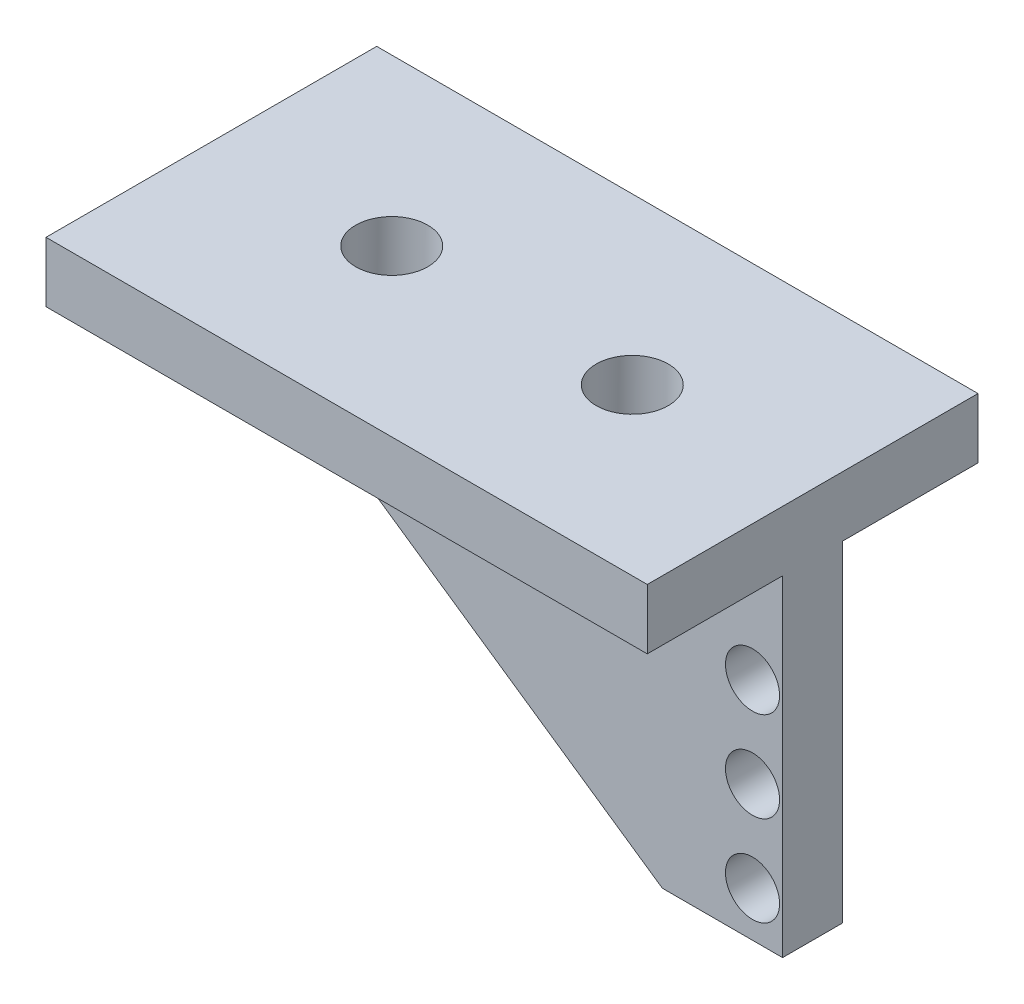
SolidWorks part; units mm, degrees
ref_plane "Front Plane" through (0, 0, 0) normal (0, 0, 1) x (1, 0, 0)
ref_plane "Top Plane" through (0, 0, 0) normal (0, 1, 0) x (1, 0, 0)
ref_plane "Right Plane" through (0, 0, 0) normal (1, 0, 0) x (0, 0, -1)
sketch "Sketch1" plane through (0, 0, 0) normal (0, 1, 0) x (1, 0, 0)
  line L0 (-20, 5.5) -> (0, 5.5)
  line L1 (0, 5.5) -> (0, -5.5)
  line L2 (0, -5.5) -> (-20, -5.5)
  line L3 (-20, -5.5) -> (-20, 5.5)
extrude "Boss-Extrude1" add sketch "Sketch1" against normal blind 2
ref_plane "Plane1" through (0, 0, -1) normal (0, 0, 1) x (1, 0, 0)
sketch "Sketch2" plane through (0, 0, -1) normal (0, 0, 1) x (1, 0, 0)
  line L0 (0, 0) -> (0, -13)
  line L1 (0, -13) -> (-4, -13)
  line L2 (-4, -13) -> (-20, -2)
  line L3 (-20, -2) -> (-20, 0)
  line L4 (-20, 0) -> (0, 0)
extrude "Boss-Extrude2" add sketch "Sketch2" along normal blind 2
ref_plane "Plane2" through (0, 0, -1) normal (0, 0, 1) x (1, 0, 0)
sketch "Sketch3" plane through (0, 0, -1) normal (0, 0, 1) x (1, 0, 0)
  circle A0 centre (-1, -5.5) radius 0.9
  circle A1 centre (-1, -8.5) radius 0.9
  circle A2 centre (-1, -11.5) radius 0.9
extrude "Cut-Extrude1" cut sketch "Sketch3" along normal blind 2
sketch "Sketch4" plane through (0, 0, 0) normal (0, 1, 0) x (1, 0, 0)
  circle A0 centre (-6, 0) radius 1.2
  circle A1 centre (-14, 0) radius 1.2
extrude "Cut-Extrude2" cut sketch "Sketch4" against normal blind 2
